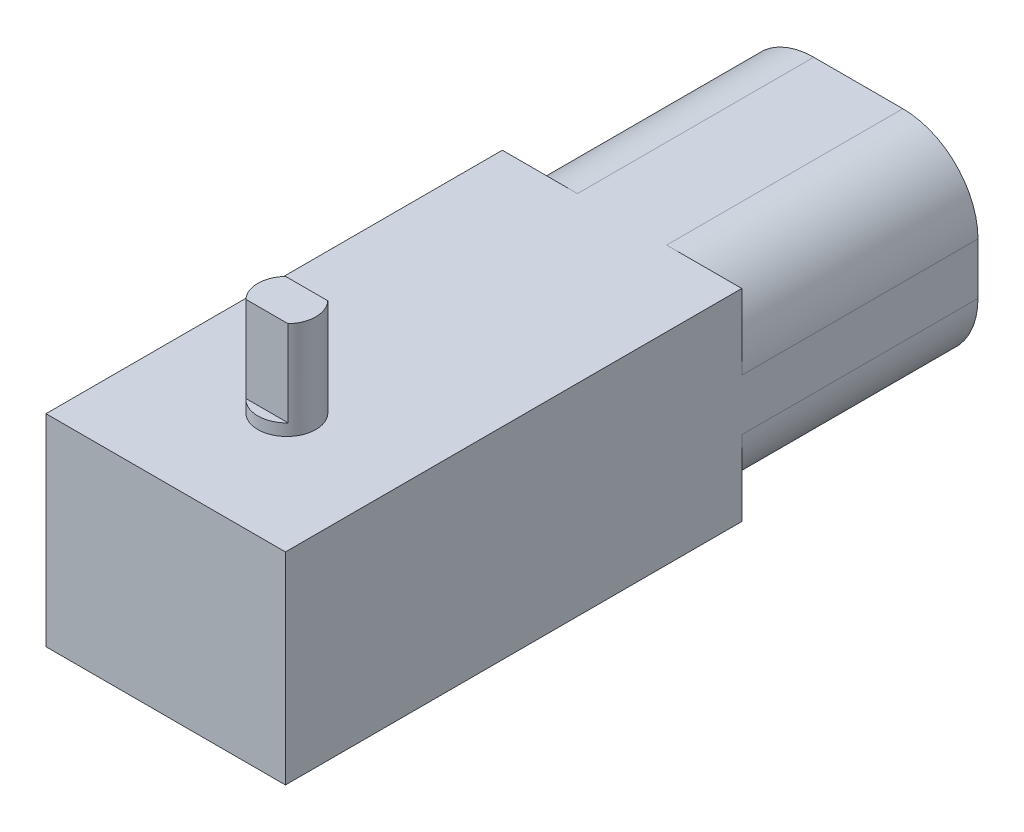
SolidWorks part; units mm, degrees
ref_plane "前视基准面" through (0, 0, 0) normal (0, 0, 1) x (1, 0, 0)
ref_plane "上视基准面" through (0, 0, 0) normal (0, 1, 0) x (1, 0, 0)
ref_plane "右视基准面" through (0, 0, 0) normal (1, 0, 0) x (0, 0, -1)
sketch "草图1" plane through (0, 0, 0) normal (0, 1, 0) x (1, 0, 0)
  line L1 (-11.15, 32.25) -> (11.15, 32.25)
  line L2 (-11.15, 32.25) -> (-11.15, -32.25)
  line L3 (-11.15, -32.25) -> (11.15, -32.25)
  line L4 (11.15, 32.25) -> (11.15, -32.25)
  line L5 (-11.15, 32.25) -> (11.15, -32.25) construction
  line L6 (-11.15, -32.25) -> (11.15, 32.25) construction
  point P0 (0, 0)
  dimension "D1" = 22.3
  dimension "D2" = 64.5
extrude "凸台-拉伸1" add sketch "草图1" along normal blind 18.8
sketch "草图2" plane through (0, 18.8, 0) normal (0, 1, 0) x (1, 0, 0)
  line L0 (0, -32.25) -> (0, -20.97) construction
  line L1 (-11.15, -32.25) -> (11.15, -32.25) construction
  circle A0 centre (0, -20.97) radius 2.7
  dimension "D2" = 5.4
  dimension "D1" = 11.28
extrude "凸台-拉伸2" add sketch "草图2" along normal blind 9.1
sketch "草图3" plane through (0, 27.9, 0) normal (0, 1, 0) x (1, 0, 0)
  line L0 (-3.8545, -19.12) -> (-3.8545, -17.6935)
  line L1 (-3.8545, -19.12) -> (3.8545, -19.12)
  line L3 (-3.8545, -22.82) -> (3.8545, -22.82)
  line L7 (-3.8545, -17.6935) -> (3.8545, -17.6935)
  line L8 (3.8545, -17.6935) -> (3.8545, -19.12)
  line L9 (3.8545, -22.82) -> (3.8545, -24.4193)
  line L10 (3.8545, -24.4193) -> (-3.8545, -24.4193)
  line L11 (-3.8545, -24.4193) -> (-3.8545, -22.82)
  point P0 (0, -20.97)
  dimension "D1" = 3.7
extrude "切除-拉伸1" cut sketch "草图3" against normal blind 8
sketch "草图4" plane through (0, 0, -32.25) normal (0, 0, -1) x (-1, 0, 0)
  line L1 (-4.15, 0) -> (4.15, 0)
  line L2 (-11.15, 7) -> (-11.15, 11.8)
  line L3 (-4.15, 18.8) -> (4.15, 18.8)
  line L4 (11.15, 7) -> (11.15, 11.8)
  line L5 (-11.15, 0) -> (11.15, 18.8) construction
  line L6 (-11.15, 18.8) -> (11.15, 0) construction
  line L7 (-11.15, 18.8) -> (11.15, 18.8)
  line L8 (-11.15, 18.8) -> (-11.15, 0)
  line L9 (-11.15, 0) -> (11.15, 0)
  line L10 (11.15, 18.8) -> (11.15, 0)
  line L11 (-11.15, 18.8) -> (11.15, 0) construction
  line L12 (-11.15, 0) -> (11.15, 18.8) construction
  arc A0 (4.15, 18.8) -> (11.15, 11.8) centre (4.15, 11.8) cw
  arc A1 (11.15, 7) -> (4.15, 0) centre (4.15, 7) cw
  arc A2 (-4.15, 0) -> (-11.15, 7) centre (-4.15, 7) cw
  arc A3 (-11.15, 11.8) -> (-4.15, 18.8) centre (-4.15, 11.8) cw
  point P0 (0, 9.4)
  point P18 (0, 9.4)
  line M1 (-11.15, 0) -> (11.15, 0)
  line M2 (11.15, 0) -> (11.15, 18.8)
  line M3 (11.15, 18.8) -> (-11.15, 18.8)
  line M4 (-11.15, 18.8) -> (-11.15, 0)
  dimension "D1" = 7
extrude "切除-拉伸2" cut sketch "草图4" against normal blind 22 contours A1 M2 M1 | A0 M3 M2 | A2 M1 M4 | A3 M4 M3
